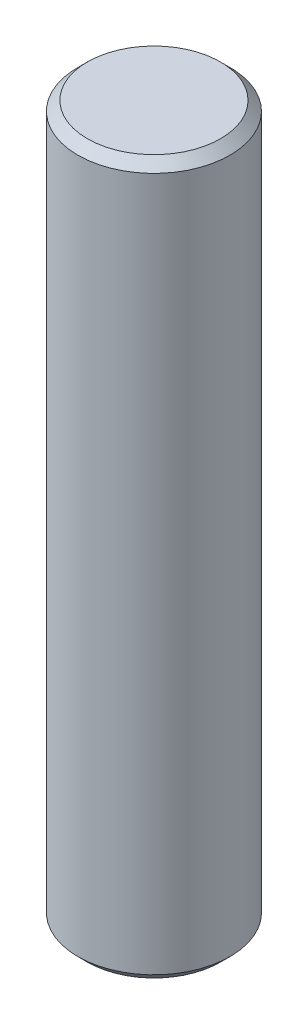
SolidWorks part; units mm, degrees
material "AISI Type A2 Tool Steel"
ref_plane "Front Plane" through (0, 0, 0) normal (0, 0, 1) x (1, 0, 0)
ref_plane "Top Plane" through (0, 0, 0) normal (0, 1, 0) x (1, 0, 0)
ref_plane "Right Plane" through (0, 0, 0) normal (1, 0, 0) x (0, 0, -1)
sketch "Sketch1" plane through (0, 0, 0) normal (0, 1, 0) x (1, 0, 0)
  circle A0 centre (0, 0) radius 16
  dimension "D1" = 32
extrude "Boss-Extrude1" add sketch "Sketch1" along normal blind 150
chamfer "Chamfer1" distance 2 angle 45 2 edges at (0, 0, 16) (0, 150, 16)
